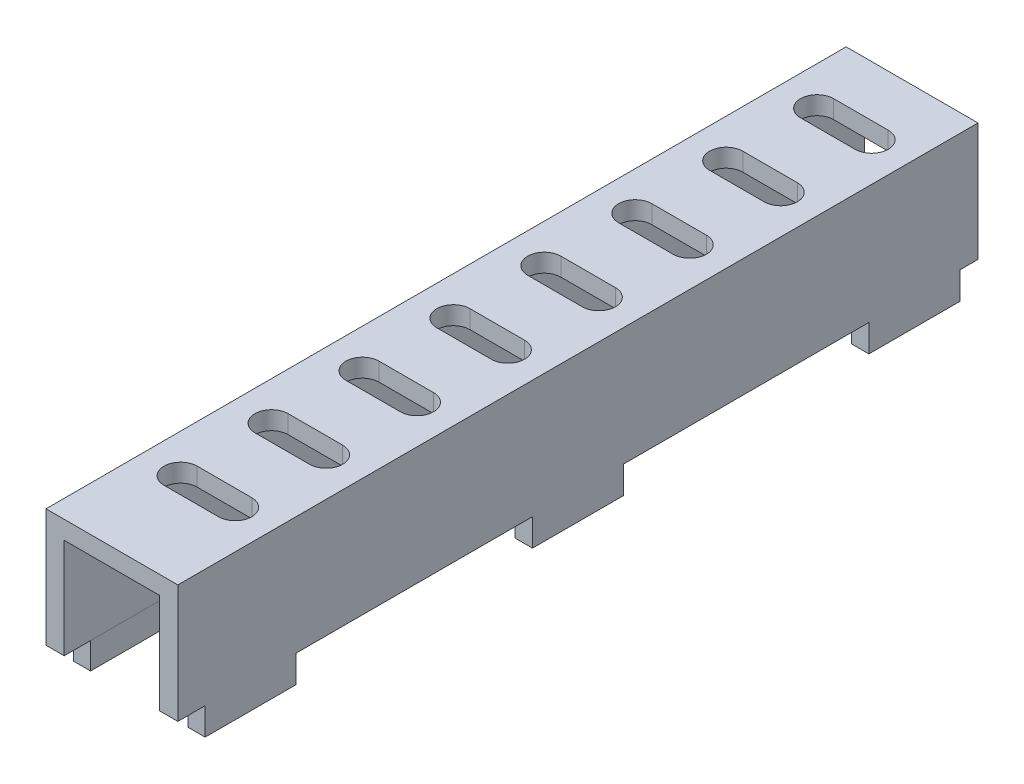
SolidWorks part; units mm, degrees
ref_plane "前视基准面" through (0, 0, 0) normal (0, 0, 1) x (1, 0, 0)
ref_plane "上视基准面" through (0, 0, 0) normal (0, 1, 0) x (1, 0, 0)
ref_plane "右视基准面" through (0, 0, 0) normal (1, 0, 0) x (0, 0, -1)
other "Configuration Table"
sketch "草图1" plane through (0, 0, 0) normal (0, 0, 1) x (1, 0, 0)
  line L0 (0, -35.3086) -> (0, 74.5598) construction
  line L1 (-7.25, 0) -> (-7.25, 13)
  line L2 (-7.25, 13) -> (7.25, 13)
  line L3 (7.25, 13) -> (7.25, 0)
  line L4 (7.25, 0) -> (5.25, 0)
  line L5 (5.25, 0) -> (5.25, 11)
  line L6 (5.25, 11) -> (-5.25, 11)
  line L7 (-5.25, 11) -> (-5.25, 0)
  line L8 (-5.25, 0) -> (-7.25, 0)
  point P9 (0, 11)
  dimension "D1" = 2
  dimension "D2" = 10.5
  dimension "D3" = 11
  dimension "D4" = 2
  dimension "D5" = 2
  dimension "13" = 13
extrude "凸台-拉伸1" add sketch "草图1" along normal blind 88
sketch "草图2" plane through (0, 13, 0) normal (0, 1, 0) x (1, 0, 0)
  line L0 (-3, -7.4463) -> (3, -7.4463) construction
  line L1 (-3, -5.6218) -> (3, -5.6218)
  line L2 (-3, -9.2709) -> (3, -9.2709)
  line L3 (0, 42.9356) -> (0, -57.8283) construction
  line L4 (-3, -17.4463) -> (3, -17.4463) construction
  line L5 (-3, -15.6218) -> (3, -15.6218)
  line L6 (-3, -19.2709) -> (3, -19.2709)
  line L7 (-3, -27.4463) -> (3, -27.4463) construction
  line L8 (-3, -25.6218) -> (3, -25.6218)
  line L9 (-3, -29.2709) -> (3, -29.2709)
  line L10 (-3, -37.4463) -> (3, -37.4463) construction
  line L11 (-3, -35.6218) -> (3, -35.6218)
  line L12 (-3, -39.2709) -> (3, -39.2709)
  line L13 (-3, -47.4463) -> (3, -47.4463) construction
  line L14 (-3, -45.6218) -> (3, -45.6218)
  line L15 (-3, -49.2709) -> (3, -49.2709)
  line L16 (-3, -57.4463) -> (3, -57.4463) construction
  line L17 (-3, -55.6218) -> (3, -55.6218)
  line L18 (-3, -59.2709) -> (3, -59.2709)
  line L19 (-3, -67.4463) -> (3, -67.4463) construction
  line L20 (-3, -65.6218) -> (3, -65.6218)
  line L21 (-3, -69.2709) -> (3, -69.2709)
  line L22 (-3, -77.4463) -> (3, -77.4463) construction
  line L23 (-3, -75.6218) -> (3, -75.6218)
  line L24 (-3, -79.2709) -> (3, -79.2709)
  arc A0 (-3, -5.6218) -> (-3, -9.2709) centre (-3, -7.4463) ccw
  arc A1 (3, -9.2709) -> (3, -5.6218) centre (3, -7.4463) ccw
  arc A2 (-3, -15.6218) -> (-3, -19.2709) centre (-3, -17.4463) ccw
  arc A3 (3, -19.2709) -> (3, -15.6218) centre (3, -17.4463) ccw
  arc A4 (-3, -25.6218) -> (-3, -29.2709) centre (-3, -27.4463) ccw
  arc A5 (3, -29.2709) -> (3, -25.6218) centre (3, -27.4463) ccw
  arc A6 (-3, -35.6218) -> (-3, -39.2709) centre (-3, -37.4463) ccw
  arc A7 (3, -39.2709) -> (3, -35.6218) centre (3, -37.4463) ccw
  arc A8 (-3, -45.6218) -> (-3, -49.2709) centre (-3, -47.4463) ccw
  arc A9 (3, -49.2709) -> (3, -45.6218) centre (3, -47.4463) ccw
  arc A10 (-3, -55.6218) -> (-3, -59.2709) centre (-3, -57.4463) ccw
  arc A11 (3, -59.2709) -> (3, -55.6218) centre (3, -57.4463) ccw
  arc A12 (-3, -65.6218) -> (-3, -69.2709) centre (-3, -67.4463) ccw
  arc A13 (3, -69.2709) -> (3, -65.6218) centre (3, -67.4463) ccw
  arc A14 (-3, -75.6218) -> (-3, -79.2709) centre (-3, -77.4463) ccw
  arc A15 (3, -79.2709) -> (3, -75.6218) centre (3, -77.4463) ccw
  point P2 (0, -7.4463)
  point P13 (0, -17.4463)
  point P20 (0, -27.4463)
  point P27 (0, -37.4463)
  point P34 (0, -47.4463)
  point P40 (0, -57.4463)
  point P47 (0, -67.4463)
  point P54 (0, -77.4463)
  dimension "D1" = 6
  dimension "D2" = 8
extrude "切除-拉伸1" cut sketch "草图2" against normal blind 55
sketch "草图4" plane through (0, 0, 0) normal (0, -1, 0) x (1, 0, 0)
  line L0 (0, 0) -> (0, 47.2336) construction
  line L1 (5.35, 85) -> (7.25, 85)
  line L3 (7.25, 88) -> (7.25, 0) construction
  line L4 (7.25, 85) -> (7.25, 75)
  line L5 (7.25, 75) -> (5.35, 75)
  line L7 (5.35, 75) -> (5.35, 85)
  line L8 (5.25, 88) -> (7.25, 88) construction
  line L9 (5.35, 49) -> (7.25, 49)
  line L10 (5.35, 49) -> (5.35, 39)
  line L11 (5.35, 39) -> (7.25, 39)
  line L12 (7.25, 49) -> (7.25, 39)
  line L13 (5.35, 12) -> (7.25, 12)
  line L14 (5.35, 12) -> (5.35, 2)
  line L15 (5.35, 2) -> (7.25, 2)
  line L16 (7.25, 12) -> (7.25, 2)
  dimension "D1" = 10
  dimension "D2" = 3
  dimension "D3" = 10
  dimension "D4" = 1.9
  dimension "D5" = 26
  dimension "D6" = 27
  dimension "D7" = 10
  dimension "D8" = 1.9
  dimension "D9" = 1.9
extrude "凸台-拉伸2" add sketch "草图4" along normal blind 3
mirror "镜向1" about plane through (0, 0, 0) normal (1, 0, 0) of "凸台-拉伸2"
